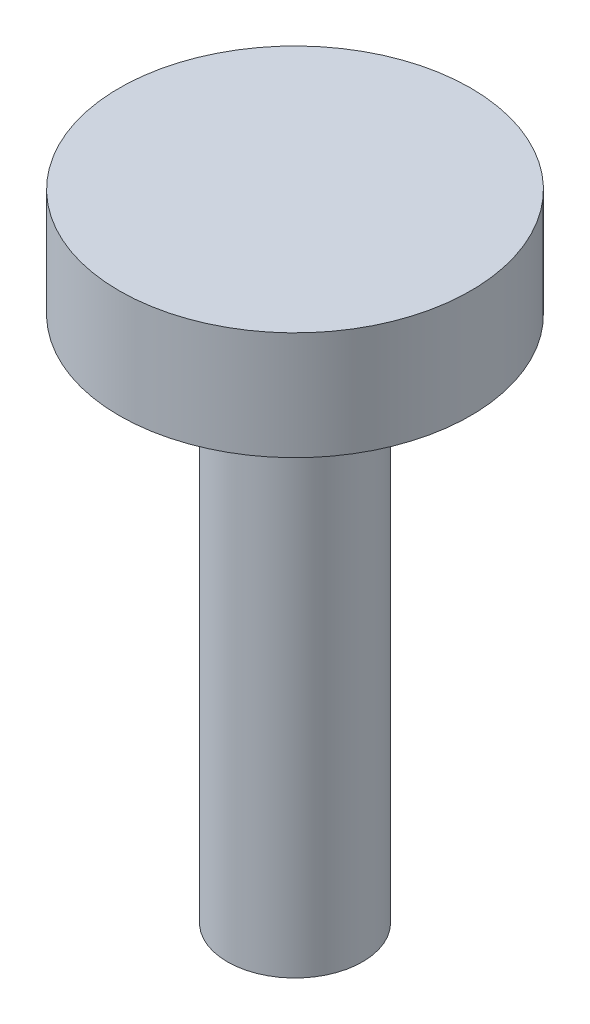
SolidWorks part; units mm, degrees
ref_plane "Front Plane" through (0, 0, 0) normal (0, 0, 1) x (1, 0, 0)
ref_plane "Top Plane" through (0, 0, 0) normal (0, 1, 0) x (1, 0, 0)
ref_plane "Right Plane" through (0, 0, 0) normal (1, 0, 0) x (0, 0, -1)
sketch "Sketch1" plane through (0, 0, 0) normal (0, 1, 0) x (1, 0, 0)
  circle A0 centre (0, 0) radius 1
  dimension "D1" = 2
extrude "Boss-Extrude1" add sketch "Sketch1" along normal blind 7.8
sketch "Sketch2" plane through (0, 7.8, 0) normal (0, 1, 0) x (1, 0, 0)
  circle A0 centre (0, 0) radius 2.6
  dimension "D1" = 5.2
extrude "Boss-Extrude2" add sketch "Sketch2" along normal blind 1.6
equation "\"D1@Boss-Extrude2\"=9.4-\"D1@Boss-Extrude1\""
